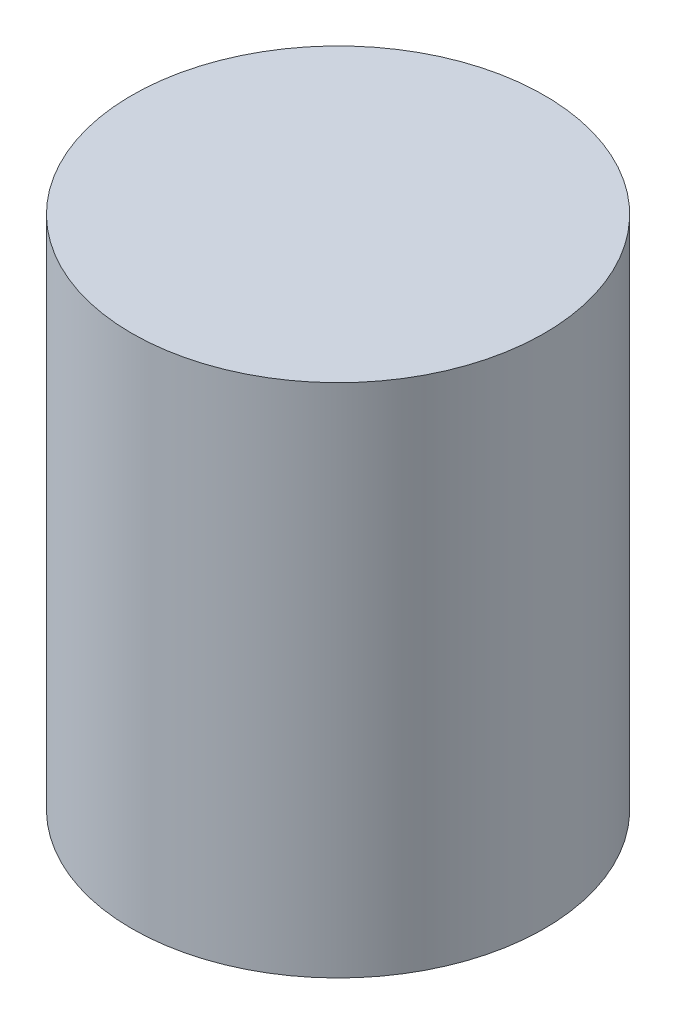
SolidWorks part; units mm, degrees
material "Silicon"
ref_plane "Front Plane" through (0, 0, 0) normal (0, 0, 1) x (1, 0, 0)
ref_plane "Top Plane" through (0, 0, 0) normal (0, 1, 0) x (1, 0, 0)
ref_plane "Right Plane" through (0, 0, 0) normal (1, 0, 0) x (0, 0, -1)
sketch "Drogue Chute Profile" plane through (0, 0, 0) normal (0, 1, 0) x (1, 0, 0)
  circle A0 centre (0, 0) radius 50.8
  dimension "D1" = 101.6
extrude "Drogue Chute Body" add sketch "Drogue Chute Profile" along normal blind 127
equation "\"Packed Diameter\"= 4"
equation "\"Packed Length\" = 5"
equation "\"D1@Drogue Chute Profile\" = \"Packed Diameter\""
equation "\"D1@Drogue Chute Body\" = \"Packed Length\""
